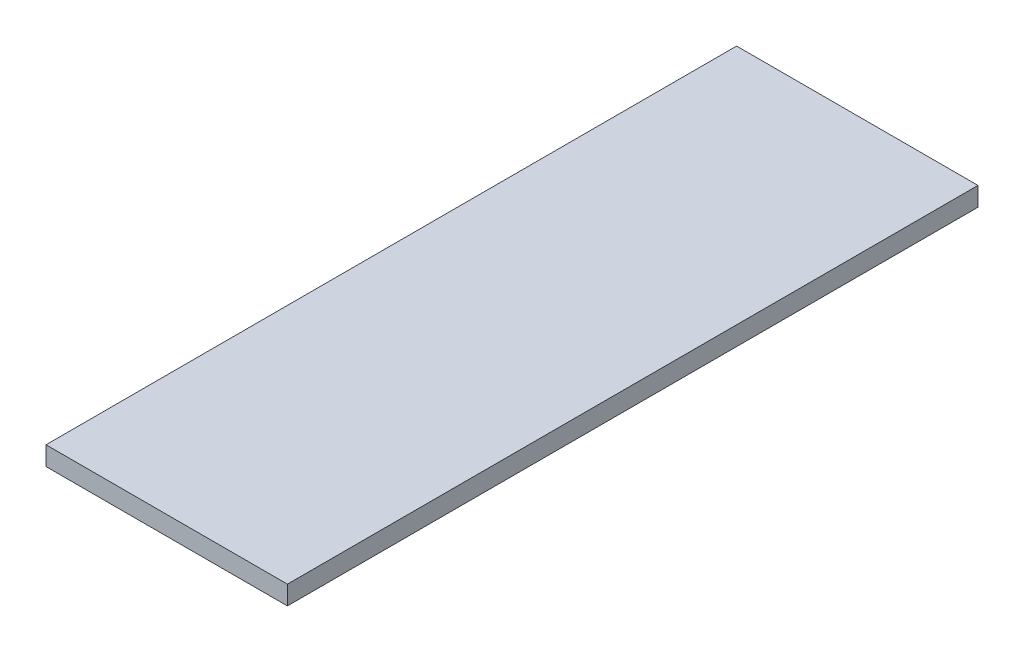
SolidWorks part; units mm, degrees
ref_plane "Front Plane" through (0, 0, 0) normal (0, 0, 1) x (1, 0, 0)
ref_plane "Top Plane" through (0, 0, 0) normal (0, 1, 0) x (1, 0, 0)
ref_plane "Right Plane" through (0, 0, 0) normal (1, 0, 0) x (0, 0, -1)
sketch "Sketch1" plane through (0, 0, 0) normal (0, 0, 1) x (1, 0, 0)
  line L1 (18, 22.86) -> (-212, 22.86)
  line L2 (18, 22.86) -> (18, 40.86)
  line L3 (18, 40.86) -> (-212, 40.86)
  line L4 (-212, 22.86) -> (-212, 40.86)
  dimension "D1" = 18
  dimension "D2" = 230
extrude "Boss-Extrude1" add sketch "Sketch1" against normal blind 650
sketch "Sketch2" plane through (0, 0, -650) normal (0, 0, -1) x (-1, 0, 0)
  line L0 (212, 40.86) -> (-18, 40.86) construction
  line L1 (212, 22.86) -> (-18, 22.86)
  line L2 (212, 22.86) -> (212, 40.86)
  line L3 (212, 40.86) -> (-18, 40.86)
  line L4 (-18, 22.86) -> (-18, 40.86)
  line L5 (-18, 40.86) -> (-18, 22.86) construction
extrude "Boss-Extrude2" add sketch "Sketch2" along normal offset from surface (8 mm away) 18
